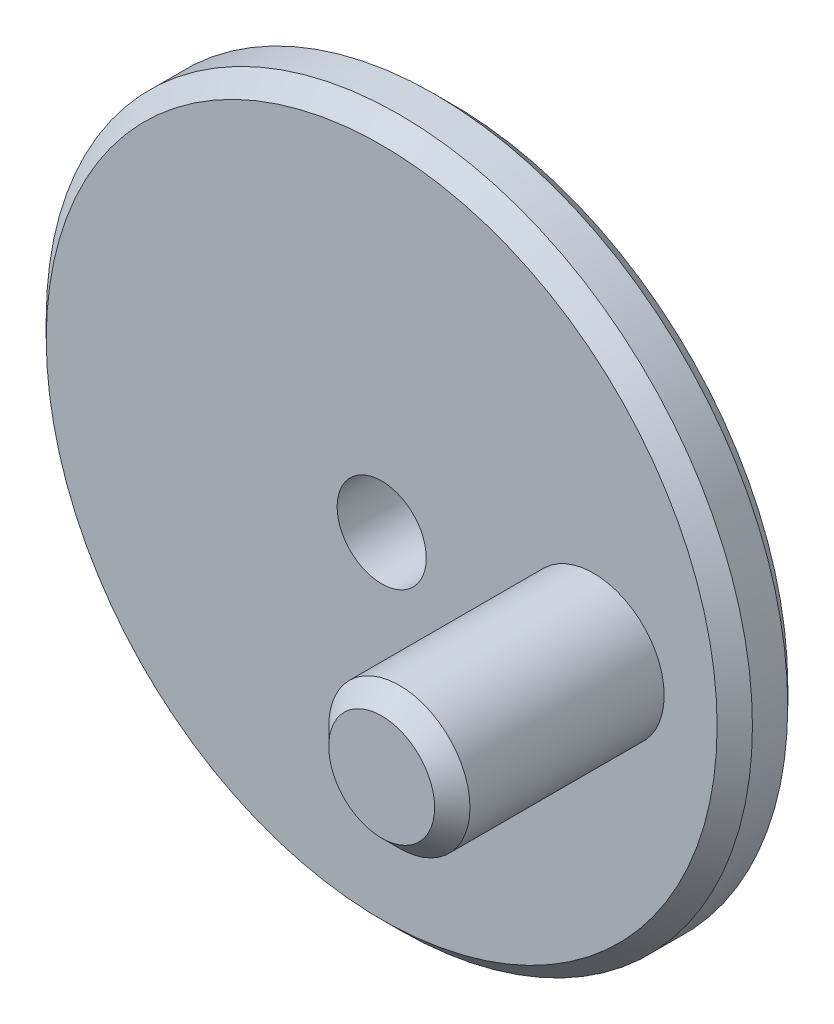
SolidWorks part; units mm, degrees
ref_plane "Front Plane" through (0, 0, 0) normal (0, 0, 1) x (1, 0, 0)
ref_plane "Top Plane" through (0, 0, 0) normal (0, 1, 0) x (1, 0, 0)
ref_plane "Right Plane" through (0, 0, 0) normal (1, 0, 0) x (0, 0, -1)
sketch "Sketch1" plane through (0, 0, 0) normal (0, 0, 1) x (1, 0, 0)
  circle A0 centre (0, 0) radius 20
  dimension "D1" = 40
extrude "Boss-Extrude1" add sketch "Sketch1" along normal mid plane 4
sketch "Sketch2" plane through (0, 0, 2) normal (0, 0, 1) x (1, 0, 0)
  circle A0 centre (12, 0) radius 4
  dimension "D2" = 8
  dimension "D1" = 12
extrude "Boss-Extrude2" add sketch "Sketch2" along normal blind 12
sketch "Sketch3" plane through (0, 0, -2) normal (0, 0, -1) x (-1, 0, 0)
  circle A0 centre (0, 0) radius 2.525
  dimension "D1" = 5.05
extrude "Cut-Extrude1" cut sketch "Sketch3" against normal up to next
chamfer "Chamfer2" distance 1 angle 45 3 edges at (20, 0, -2) (20, 0, 2) (16, 0, 14)
